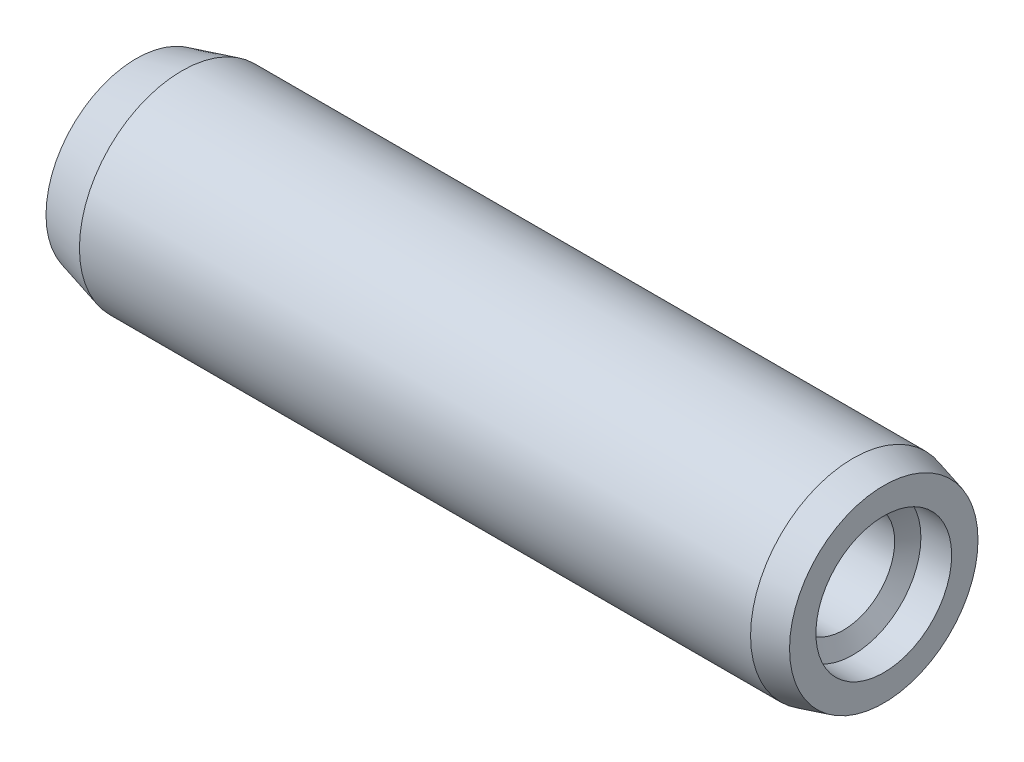
SolidWorks part; units mm, degrees
ref_plane "Plan1" through (0, 0, 0) normal (0, 0, 1) x (1, 0, 0)
ref_plane "Plan2" through (0, 0, 0) normal (0, 1, 0) x (1, 0, 0)
ref_plane "Plan3" through (0, 0, 0) normal (1, 0, 0) x (0, 0, -1)
sketch "Esquisse1" plane through (0, 0, 0) normal (0, 0, 1) x (1, 0, 0)
  line L0 (-7.0625, 0) -> (36.9107, 0) construction
  line L1 (0.8171, 3.5223) -> (2.6, 4)
  line L2 (2.6, 4) -> (28.8, 4)
  line L3 (28.8, 4) -> (30, 3.6785)
  line L4 (30, 3.6785) -> (30, 0)
  line L5 (30, 0) -> (0, 0)
  arc A0 (0.8171, 3.5223) -> (0, 0) centre (8, 0) ccw
  dimension "D1" = 8
  dimension "D2" = 30
  dimension "D3" = 15
  dimension "D4" = 1.2
  dimension "D5" = 2.6
  dimension "D6" = 15
  dimension "D7" = 4
revolve "Base-Révolution" add sketch "Esquisse1" angle 360 about L0
hole_wizard "Perçage1" positions "Esquisse4" profile "Esquisse3"
sketch "Esquisse4" plane through (30, 0, 0) normal (1, 0, 0) x (0, 0, -1)
  point P0 (0, 0)
sketch "Esquisse3" plane through (30, 0, 0) normal (0, 1, 0) x (0, 0, -1)
  line L0 (0, 0) -> (0, 13.1547)
  line L1 (0, 13.1547) -> (2, 12)
  line L2 (2, 12) -> (2, 0)
  line L4 (2, 0) -> (0, 0)
  line L6 (0, 13.1547) -> (-2, 12) construction
  line L7 (0, -4.2442) -> (0, 117.3081) construction
  dimension "Diamètre" = 4
  dimension "Profondeur" = 12
  dimension "Angle" = 120
cosmetic thread "Représentation de filetage1"
hole_wizard "Perçage2" positions "Esquisse6" profile "Esquisse5"
sketch "Esquisse6" plane through (30, 0, 0) normal (1, 0, 0) x (0, 0, -1)
  point P0 (0, 0)
sketch "Esquisse5" plane through (30, 0, 0) normal (0, 1, 0) x (0, 0, -1)
  line L0 (0, 0) -> (0, 2.73)
  line L1 (0, 2.73) -> (2.65, 1.2)
  line L2 (2.65, 1.2) -> (2.65, 0)
  line L4 (2.65, 0) -> (0, 0)
  line L6 (0, 2.73) -> (-2.65, 1.2) construction
  line L7 (0, -4.2442) -> (0, 117.3081) construction
  dimension "Diamètre" = 5.3
  dimension "Profondeur" = 1.2
  dimension "Angle" = 120
